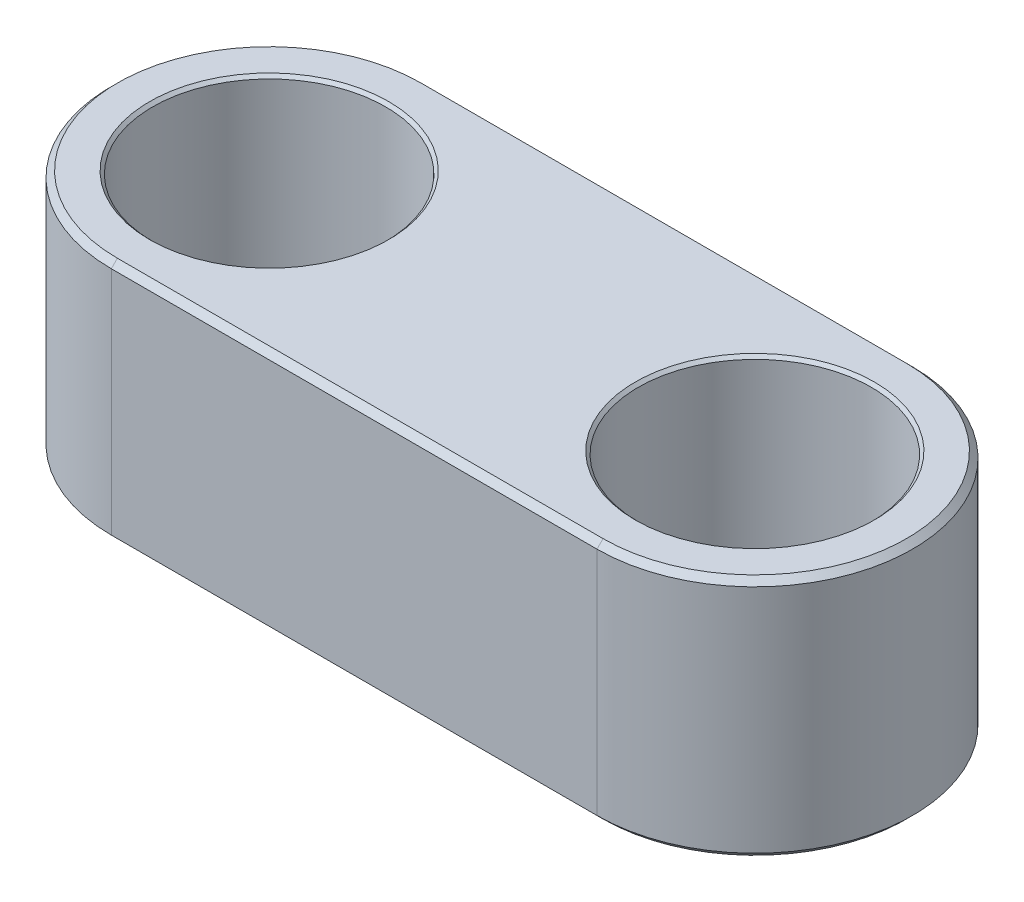
SolidWorks part; units mm, degrees
ref_plane "Front Plane" through (0, 0, 0) normal (0, 0, 1) x (1, 0, 0)
ref_plane "Top Plane" through (0, 0, 0) normal (0, 1, 0) x (1, 0, 0)
ref_plane "Right Plane" through (0, 0, 0) normal (1, 0, 0) x (0, 0, -1)
sketch "Sketch1" plane through (0, 0, 0) normal (0, 1, 0) x (1, 0, 0)
  line L0 (0, 0) -> (80, 0) construction
  line L1 (0, 26) -> (80, 26)
  line L2 (0, -26) -> (80, -26)
  arc A0 (0, 26) -> (0, -26) centre (0, 0) ccw
  arc A1 (80, -26) -> (80, 26) centre (80, 0) ccw
  circle A2 centre (0, 0) radius 19.2
  circle A3 centre (80, 0) radius 19.2
  point P3 (40, 0)
  dimension "D1" = 38.4
  dimension "D2" = 26
  dimension "D3" = 80
extrude "Boss-Extrude1" add sketch "Sketch1" along normal blind 40
shell "Shell1" thickness 6
chamfer "Chamfer1" distance 1 angle 45 8 edges at (40, 0, -26) (-26, 0, 0) (106, 0, 0) (40, 0, 26) (106, 40, 0) (40, 40, -26) (40, 40, 26) (-26, 40, 0)
sketch "Sketch2" plane through (0, 40, 0) normal (0, 1, 0) x (1, 0, 0)
  line L0 (40, 15.5521) -> (40, -13.926)
  line L1 (40, 15.5521) -> (40, 20) construction
  line L2 (64.669, 20) -> (15.331, 20) construction
rib "Rib1" sketch "Sketch2" sketch "Sketch2" thickness 6 extrusion direction normal to sketch draft on no parameters "D1"=6
fillet "Fillet1" radius 1 6 edges at (64.669, 23, 20) (64.669, 23, -20) (37, 23, 20) (15.331, 23, 20) (37, 23, -20) (15.331, 23, -20)
sketch "Sketch3" plane through (0, 40, 0) normal (0, 1, 0) x (1, 0, 0)
  line L0 (18.04, 20) -> (61.96, 20)
  line L1 (18.04, -20) -> (61.96, -20)
  arc A0 (62.6486, 18.2748) -> (61.96, 20) centre (61.96, 19) ccw construction
  arc A1 (62.6486, 18.2748) -> (62.6486, -18.2748) centre (80, 0) ccw construction
  arc A2 (61.96, -20) -> (62.6486, -18.2748) centre (61.96, -19) ccw construction
  arc A3 (17.3514, -18.2748) -> (18.04, -20) centre (18.04, -19) ccw construction
  arc A4 (18.04, 20) -> (17.3514, 18.2748) centre (18.04, 19) ccw construction
  arc A5 (17.3514, -18.2748) -> (17.3514, 18.2748) centre (0, 0) ccw construction
  arc A6 (62.6486, 18.2748) -> (61.96, 20) centre (61.96, 19) ccw
  arc A7 (62.6486, 18.2748) -> (62.6486, -18.2748) centre (80, 0) ccw
  arc A8 (61.96, -20) -> (62.6486, -18.2748) centre (61.96, -19) ccw
  arc A9 (17.3514, -18.2748) -> (18.04, -20) centre (18.04, -19) ccw
  arc A10 (18.04, 20) -> (17.3514, 18.2748) centre (18.04, 19) ccw
  arc A11 (17.3514, -18.2748) -> (17.3514, 18.2748) centre (0, 0) ccw
extrude "Boss-Extrude2" add sketch "Sketch3" against normal blind 3
chamfer "Chamfer2" distance 0.5 angle 45 4 edges at (80, 40, 19.2) (80, 0, 19.2) (0, 0, 19.2) (0, 40, 19.2)
